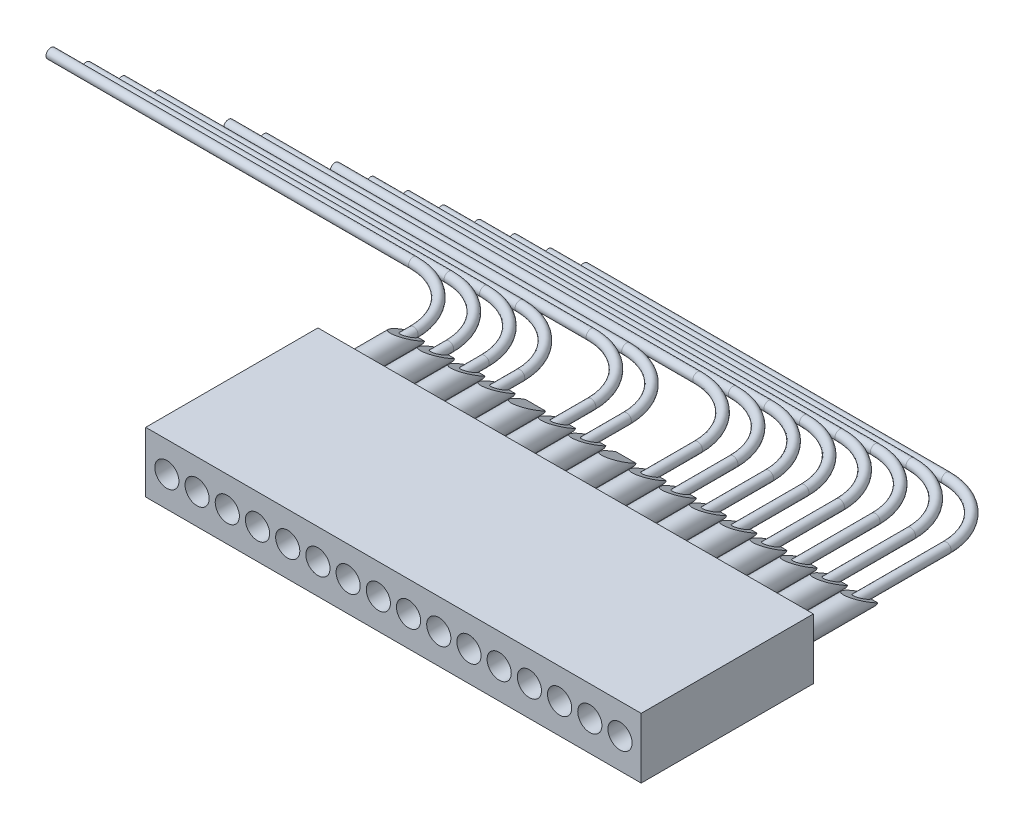
SolidWorks part; units mm, degrees
material "ASTM A36 Steel"
ref_plane "Front Plane" through (0, 0, 0) normal (0, 0, 1) x (1, 0, 0)
ref_plane "Top Plane" through (0, 0, 0) normal (0, 1, 0) x (1, 0, 0)
ref_plane "Right Plane" through (0, 0, 0) normal (1, 0, 0) x (0, 0, -1)
ref_plane "Plane1" through (0, 0, -9.144) normal (0, 0, 1) x (1, 0, 0)
sketch "Sketch1" plane through (0, 0, 0) normal (0, 1, 0) x (1, 0, 0)
  line L0 (-9.525, 7.239) -> (0.889, 9.0753) construction
  line L1 (-19.939, 7.239) -> (0.889, 7.239)
  line L2 (-19.939, 7.239) -> (-19.939, 0)
  line L3 (-19.939, 0) -> (0.889, 0)
  line L4 (0.889, 7.239) -> (0.889, 0)
  point P6 (-19.05, 0)
  dimension "D1" = 7.239
  dimension "D2" = 0.889
  dimension "D3" = 10
  dimension "D4" = 0.889
  dimension "D5" = 19.05
extrude "Boss-Extrude1" add sketch "Sketch1" against normal mid plane 2.54
sketch "Sketch8" plane through (0, 0, 0) normal (0, 1, 0) x (1, 0, 0)
  line L0 (0.508, -0.7894) -> (0.508, 2.54)
  line L1 (0.508, 2.54) -> (0, 2.54)
  line L2 (0, 2.54) -> (0, -0.7894)
  line L3 (0, -0.7894) -> (0.508, -0.7894)
  line L4 (0, -0.7894) -> (0, -1.9625) construction
  dimension "D1" = 1.016
  dimension "D2" = 2.54
revolve "Cut-Revolve1" cut sketch "Sketch8" angle 360 about L4
pattern_linear "LPattern4" count 16 spacing 1.27 along (-1, 0, 0) of "Cut-Revolve1"
sketch "Sketch3" plane through (0, 0, 0) normal (0, 1, 0) x (1, 0, 0)
  line L0 (0, -2.0371) -> (0, -3.6246) construction
  line L1 (0, 10.414) -> (0.4445, 10.414)
  line L2 (0, 10.414) -> (0, 3.81)
  line L3 (0, 3.81) -> (0.254, 3.81)
  line L4 (0.4445, 10.414) -> (0.4445, 5.08)
  line L5 (-19.939, 7.239) -> (0.889, 7.239) construction
  line L6 (0.4445, 5.08) -> (0.254, 5.08)
  line L7 (0.254, 5.08) -> (0.254, 3.81)
  line L9 (-19.939, 0) -> (0.889, 0) construction
  dimension "D2" = 0.889
  dimension "D3" = 3.175
  dimension "D4" = 3.81
  dimension "D5" = 5.08
  dimension "D6" = 0.508
revolve "Revolve1" add sketch "Sketch3" angle 360 about L0
sketch "Sketch4" plane through (0, 0, 0) normal (0, 1, 0) x (1, 0, 0)
  line L0 (0, 9.144) -> (0, 13.716)
  line L1 (-2.54, 16.256) -> (-17.78, 16.256)
  line L2 (-1.397, 9.144) -> (1.397, 9.144) construction
  arc A0 (0, 13.716) -> (-2.54, 16.256) centre (-2.54, 13.716) ccw
  dimension "D2" = 2.54
  dimension "D1" = 4.572
  dimension "D3" = 15.24
pattern_linear "LPattern1" count 16 spacing 1.27 along (-1, 0, 0) of "Revolve1"
sketch "Sketch9" plane through (0, 0, 0) normal (1, 0, 0) x (0, 0, -1)
  line L0 (10.8904, 0.7636) -> (8.8373, 0.7636)
  line L1 (8.8373, 0.7636) -> (10.8904, -0.4217)
  line L2 (10.8904, -0.4217) -> (10.8904, 0.7636)
  point P2 (10.16, 0)
  dimension "D1" = 30
  dimension "D2" = 0.254
extrude "Cut-Extrude2" cut sketch "Sketch9" against normal through all and the other way through all
sketch "Sketch5" plane through (0, 0, -9.144) normal (0, 0, -1) x (-1, 0, 0)
  circle A0 centre (0, 0) radius 0.2032
  dimension "D1" = 0.4064
sweep "Sweep1" add profiles "Sketch5" path "Sketch4"
pattern_linear "LPattern2" count 17 spacing 1.2893 along (-0.9848, 0, 0.1736) skipping (8, 0), (11, 0), (16, 0) of "Sweep1"
sketch "Sketch6" plane through (0, 0, 0) normal (1, 0, 0) x (0, 0, -1)
  line L0 (0, 1.27) -> (7.239, 1.27) construction
  line L1 (2.3622, 3.556) -> (4.9022, 3.556)
  line L2 (2.3622, 3.556) -> (2.3622, 1.016)
  line L3 (2.3622, 1.016) -> (4.9022, 1.016)
  line L4 (4.9022, 3.556) -> (4.9022, 1.016)
  dimension "D1" = 2.3622
  dimension "D2" = 2.54
  dimension "D3" = 0.254
extrude "Cut-Extrude1" [suppressed] cut sketch "Sketch6" against normal mid plane 50.8
